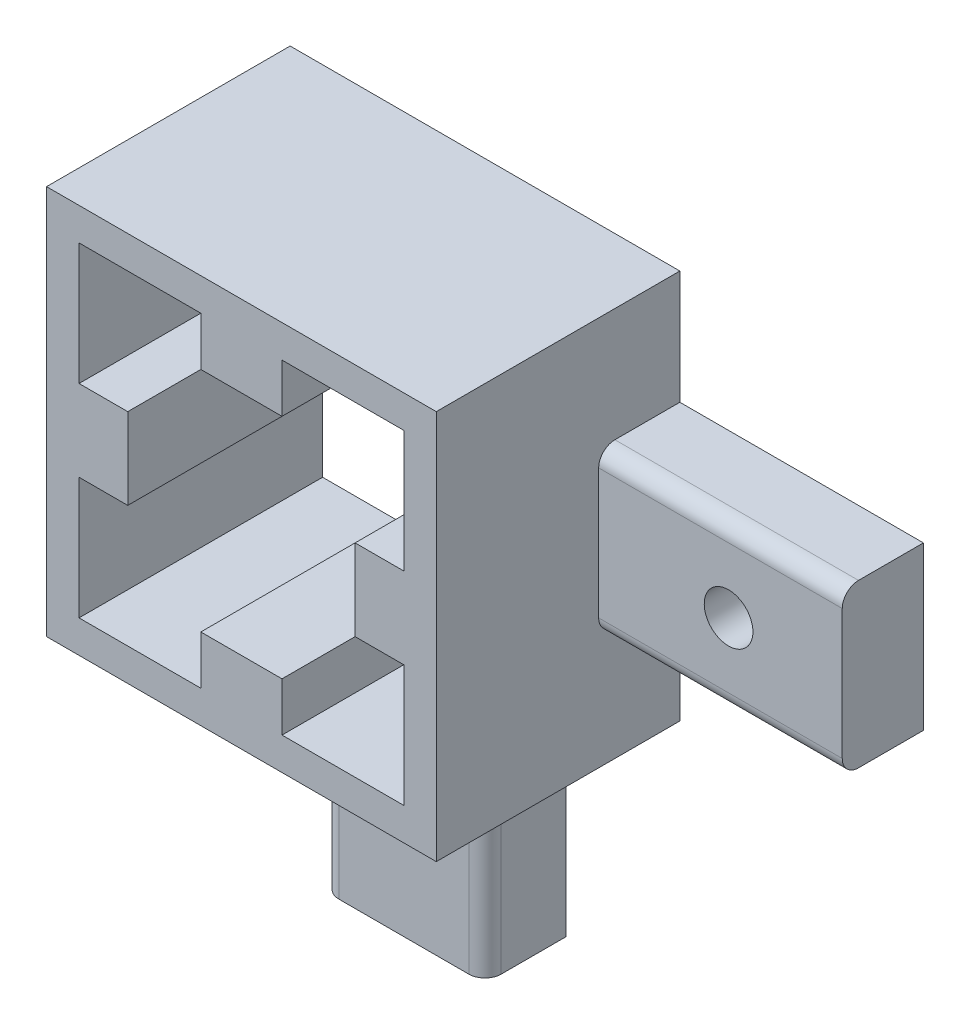
SolidWorks part; units mm, degrees
ref_plane "Front Plane" through (0, 0, 0) normal (0, 0, 1) x (1, 0, 0)
ref_plane "Top Plane" through (0, 0, 0) normal (0, 1, 0) x (1, 0, 0)
ref_plane "Right Plane" through (0, 0, 0) normal (1, 0, 0) x (0, 0, -1)
sketch "Sketch2" plane through (0, 0, 0) normal (0, 0, 1) x (1, 0, 0)
  line L0 (-2.5, 10) -> (-2.5, 7)
  line L1 (10, -10) -> (2.5, -10)
  line L2 (10, -10) -> (10, -2.5)
  line L3 (10, 10) -> (2.5, 10)
  line L4 (-10, -10) -> (-10, -2.5)
  line L5 (10, -10) -> (-10, 10) construction
  line L6 (10, 10) -> (-10, -10) construction
  line L7 (-2.5, 7) -> (2.5, 7)
  line L8 (2.5, 7) -> (2.5, 10)
  line L9 (7, 2.5) -> (7, -2.5)
  line L10 (7, -2.5) -> (10, -2.5)
  line L11 (10, 2.5) -> (7, 2.5)
  line L12 (2.5, -7) -> (-2.5, -7)
  line L13 (-2.5, -7) -> (-2.5, -10)
  line L14 (2.5, -10) -> (2.5, -7)
  line L15 (-7, -2.5) -> (-7, 2.5)
  line L16 (-7, 2.5) -> (-10, 2.5)
  line L17 (-10, -2.5) -> (-7, -2.5)
  line L18 (0, 10) -> (0, -7) construction
  line L19 (-10, 2.5) -> (-10, 10)
  line L20 (12, -12) -> (-12, -12)
  line L21 (12, -12) -> (12, 12)
  line L22 (12, 12) -> (-12, 12)
  line L23 (-12, -12) -> (-12, 12)
  line L24 (12, -12) -> (-12, 12) construction
  line L25 (12, 12) -> (-12, -12) construction
  line L26 (-2.5, 10) -> (-10, 10)
  line L27 (10, 2.5) -> (10, 10)
  line L28 (-2.5, -10) -> (-10, -10)
  point P0 (0, 0)
  point P8 (0, 7)
  point P11 (0, 0)
  dimension "D2" = 2.5
  dimension "D3" = 2.5
  dimension "D4" = 7
  dimension "D5" = 20
  dimension "D6" = 2
  dimension "D7" = 2
  dimension "D1" = 4
extrude "Boss-Extrude1" add sketch "Sketch2" along normal blind 15
sketch "Sketch3" plane through (0, -12, 0) normal (0, -1, 0) x (1, 0, 0)
  line L0 (-5, 4) -> (-5, 0)
  line L1 (-4, 5) -> (4, 5)
  line L2 (-5, 0) -> (5, 0)
  line L3 (5, 4) -> (5, 0)
  line L4 (-12, 0) -> (12, 0) construction
  line L5 (0, 0) -> (0, 9.0425) construction
  arc A0 (5, 4) -> (4, 5) centre (4, 4) ccw
  arc A1 (-5, 4) -> (-4, 5) centre (-4, 4) cw
  point P11 (0, 5)
  dimension "D2" = 1
  dimension "D1" = 5
  dimension "D3" = 10
extrude "Boss-Extrude2" add sketch "Sketch3" along normal blind 15
sketch "Sketch4" plane through (0, 0, 5) normal (0, 0, 1) x (1, 0, 0)
  line L1 (-12, -12) -> (12, -12) construction
  circle A0 centre (0, -20) radius 1.5
  dimension "D1" = 8
extrude "Cut-Extrude1" cut sketch "Sketch4" against normal up to next contours A0
sketch "Sketch5" plane through (0, 0, 0) normal (1, 0, 0) x (0, 0, -1)
  line L0 (-23.3163, 0) -> (13.6257, 0) construction
pattern_circular "CirPattern1" count 2 every 90 about axis through (0, 0, 0) along (0, 0, 1) of "Cut-Extrude1", "Boss-Extrude2"
